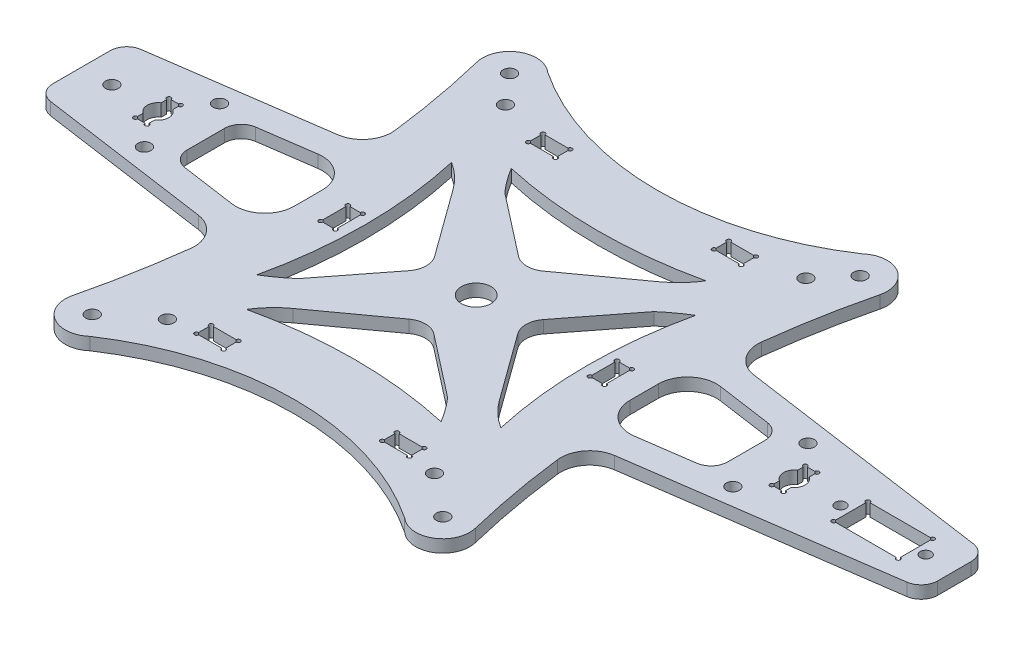
SolidWorks part; units mm, degrees
material "PPS"
ref_plane "前视基准面" through (0, 0, 0) normal (0, 0, 1) x (1, 0, 0)
ref_plane "上视基准面" through (0, 0, 0) normal (0, 1, 0) x (1, 0, 0)
ref_plane "右视基准面" through (0, 0, 0) normal (1, 0, 0) x (0, 0, -1)
sketch "草图1" plane through (0, 0, 0) normal (0, 1, 0) x (1, 0, 0)
  line L3 (-133.7177, 0) -> (146.3754, 0) construction
  line L56 (0, 96.0639) -> (0, -115.1457) construction
  line L65 (-25.5, 41.5) -> (-19, 41.5)
  line L66 (-34, 3.25) -> (-30.5, 3.25)
  line L70 (-34, 3.25) -> (-34, -3.25)
  line L76 (-34, -3.25) -> (-30.5, -3.25)
  line L80 (-30.5, 3.25) -> (-30.5, -3.25)
  line L81 (-25.5, -38) -> (-19, -38)
  line L82 (-25.5, -38) -> (-25.5, -41.5)
  line L83 (-25.5, -41.5) -> (-19, -41.5)
  line L84 (-19, -38) -> (-19, -41.5)
  line L85 (-19, 38) -> (-19, 41.5)
  line L86 (-25.5, 38) -> (-19, 38)
  line L142 (-25.5, 38) -> (-25.5, 41.5)
  line L143 (25.5, 38) -> (25.5, 41.5)
  line L144 (25.5, 38) -> (19, 38)
  line L145 (19, 38) -> (19, 41.5)
  line L146 (19, -38) -> (19, -41.5)
  line L147 (25.5, -41.5) -> (19, -41.5)
  line L148 (25.5, -38) -> (25.5, -41.5)
  line L149 (25.5, -38) -> (19, -38)
  line L150 (30.5, 3.25) -> (30.5, -3.25)
  line L151 (34, -3.25) -> (30.5, -3.25)
  line L152 (34, 3.25) -> (34, -3.25)
  line L153 (34, 3.25) -> (30.5, 3.25)
  line L154 (25.5, 41.5) -> (19, 41.5)
  line L155 (77.65, -2.1518) -> (77.65, -4)
  line L156 (74.85, 4) -> (77.65, 4)
  line L157 (74.85, 4) -> (74.85, 2.1768)
  line L158 (74.85, -4) -> (77.65, -4)
  line L159 (77.65, 4) -> (77.65, 2.1518)
  line L160 (74.85, -2.1768) -> (74.85, -4)
  line L161 (97.5, 7.6653) -> (97.5, -9.1503) construction
  line L162 (89.75, 4.1) -> (105.25, 4.1)
  line L163 (89.75, 4.1) -> (89.75, -4.1)
  line L164 (89.75, -4.1) -> (105.25, -4.1)
  line L165 (105.25, 4.1) -> (105.25, -4.1)
  line L166 (-97.5, 7.6653) -> (-97.5, -9.1503) construction
  line L171 (-74.85, -2.1768) -> (-74.85, -4)
  line L172 (-77.65, 4) -> (-77.65, 2.1518)
  line L173 (-74.85, -4) -> (-77.65, -4)
  line L174 (-74.85, 4) -> (-74.85, 2.1768)
  line L175 (-74.85, 4) -> (-77.65, 4)
  line L176 (-77.65, -2.1518) -> (-77.65, -4)
  line L177 (114.5911, 7.4683) -> (114.5911, -7.4683)
  line L178 (114.5911, 7.4683) -> (43.1936, 17.6463)
  line L179 (114.5911, -7.4683) -> (43.1936, -17.6463)
  line L183 (-24.7128, 19.184) -> (-10.803, 0)
  line L184 (19.184, 24.7128) -> (0, 10.803)
  line L185 (-24.7128, -17.8765) -> (-10.803, 0)
  line L186 (-17.8765, 24.7128) -> (0, 10.803)
  line L187 (24.7128, -19.184) -> (10.803, 0)
  line L188 (24.7128, 17.8765) -> (10.803, 0)
  line L189 (-19.184, -24.7128) -> (0, -10.803)
  line L190 (17.8765, -24.7128) -> (0, -10.803)
  line L191 (-94.5795, 10.321) -> (-94.5795, -10.321)
  line L192 (-43.1936, 17.6463) -> (-94.5795, 10.321)
  line L193 (-94.5795, -10.321) -> (-43.1936, -17.6463)
  line L195 (-64.75, -7.9571) -> (-64.75, 7.9571)
  line L196 (-64.75, 7.9571) -> (-40.25, 11.4497)
  line L197 (-40.25, 11.4497) -> (-40.25, -11.4497)
  line L198 (-64.75, -7.9571) -> (-40.25, -11.4497)
  line L199 (64.75, 7.9571) -> (40.25, 11.4497)
  line L200 (40.25, 11.4497) -> (40.25, -11.4497)
  line L201 (64.75, -7.9571) -> (40.25, -11.4497)
  line L202 (64.75, 7.9571) -> (64.75, -7.9571)
  circle A0 centre (-36, 43) radius 1.55
  circle A1 centre (-32, -42) radius 1.55
  circle A2 centre (32, -42) radius 1.55
  circle A3 centre (36, 43) radius 1.55
  circle A4 centre (42, 50) radius 1.55
  circle A5 centre (42, -50) radius 1.55
  circle A6 centre (-42, -50) radius 1.55
  circle A7 centre (-42, 50) radius 1.55
  arc A8 (74.85, 2.1768) -> (74.85, -2.1768) centre (76.2307, 0) ccw
  arc A9 (77.65, -2.1518) -> (77.65, 2.1518) centre (76.2307, 0) ccw
  circle A10 centre (107.7, 0) radius 1.3
  circle A11 centre (87.3, 0) radius 1.3
  circle A12 centre (-87.3, 0) radius 1.3 construction
  arc A14 (-77.65, -2.1518) -> (-77.65, 2.1518) centre (-76.2307, 0) cw
  arc A15 (-74.85, 2.1768) -> (-74.85, -2.1768) centre (-76.2307, 0) cw
  arc A18 (-37.7098, 54.831) -> (37.7098, 54.831) centre (0, 111.5317) ccw
  arc A20 (48.2756, 48.4632) -> (43.1936, 17.6463) centre (246.1791, 0) ccw
  arc A21 (48.2756, 48.4632) -> (37.7098, 54.831) centre (42, 50) ccw
  arc A22 (-37.7098, -54.831) -> (37.7098, -54.831) centre (0, -111.5317) cw
  arc A23 (48.2756, -48.4632) -> (43.1936, -17.6463) centre (246.1791, 0) cw
  arc A24 (48.2756, -48.4632) -> (37.7098, -54.831) centre (42, -50) cw
  arc A26 (-48.2756, -48.4632) -> (-37.7098, -54.831) centre (-42, -50) ccw
  arc A27 (-48.2756, -48.4632) -> (-43.1936, -17.6463) centre (-246.1791, 0) ccw
  arc A28 (-48.2756, 48.4632) -> (-37.7098, 54.831) centre (-42, 50) cw
  arc A30 (-48.2756, 48.4632) -> (-43.1936, 17.6463) centre (-246.1791, 0) cw
  arc A31 (-24.7128, 19.184) -> (-30.4857, 24.5725) centre (-41.4252, 7.0662) ccw
  arc A32 (-24.7128, -17.8765) -> (-30.4857, -22.0817) centre (-52.1779, 13.7617) cw
  arc A33 (-30.4857, -22.0817) -> (-30.4857, 24.5725) centre (-134.387, 1.2454) ccw
  arc A34 (-17.8765, 24.7128) -> (-22.0817, 30.4857) centre (13.7617, 52.1779) cw
  arc A35 (-22.0817, 30.4857) -> (24.5725, 30.4857) centre (1.2454, 134.387) ccw
  arc A36 (19.184, 24.7128) -> (24.5725, 30.4857) centre (7.0662, 41.4252) ccw
  arc A37 (24.7128, 17.8765) -> (30.4857, 22.0817) centre (52.1779, -13.7617) cw
  arc A38 (30.4857, 22.0817) -> (30.4857, -24.5725) centre (134.387, -1.2454) ccw
  arc A39 (24.7128, -19.184) -> (30.4857, -24.5725) centre (41.4252, -7.0662) ccw
  arc A40 (17.8765, -24.7128) -> (22.0817, -30.4857) centre (-13.7617, -52.1779) cw
  arc A41 (22.0817, -30.4857) -> (-24.5725, -30.4857) centre (-1.2454, -134.387) ccw
  arc A42 (-19.184, -24.7128) -> (-24.5725, -30.4857) centre (-7.0662, -41.4252) ccw
  circle A43 centre (70.5, 9) radius 1.55
  circle A44 centre (70.5, -9) radius 1.55
  circle A45 centre (-70.5, -9) radius 1.55
  circle A46 centre (-70.5, 9) radius 1.55
  circle A47 centre (-87.3, 0) radius 1.55
  point P81 (-34, 0)
  point P118 (0, 0)
  point P140 (-40.25, 0)
  point P149 (-64.75, 0)
  dimension "D5" = 38
  dimension "D18" = 8.2
  dimension "D24" = 3.1
  dimension "D6" = 3.1
  dimension "D11" = 50
  dimension "D15" = 74.85
  dimension "D16" = 2.6
  dimension "D17" = 15.5
  dimension "D21" = 3.1
  dimension "D1" = 6.5
  dimension "D2" = 3.5
  dimension "D3" = 30.5
  dimension "D4" = 19
  dimension "D7" = 32
  dimension "D8" = 42
  dimension "D9" = 43
  dimension "D10" = 36
  dimension "D12" = 42
  dimension "D13" = 2.8
  dimension "D14" = 4
  dimension "D19" = 2.45
  dimension "D20" = 97.5
  dimension "D22" = 9
  dimension "D23" = 70.5
  dimension "D25" = 6.55
  dimension "D26" = 5.75
  dimension "D27" = 6.25
  dimension "D28" = 4
extrude "凸台-拉伸1" add sketch "草图1" along normal blind 3
fillet "圆角1" radius 4 8 edges at (114.5911, 1.5, -7.4683) (114.5911, 1.5, 7.4683) (-94.5795, 1.5, 10.321) (-94.5795, 1.5, -10.321) (-64.75, 1.5, 7.9571) (-64.75, 1.5, -7.9571) (64.75, 1.5, 7.9571) (64.75, 1.5, -7.9571)
fillet "圆角2" radius 7 8 edges at (43.1936, 1.5, -17.6463) (43.1936, 1.5, 17.6463) (-43.1936, 1.5, 17.6463) (-43.1936, 1.5, -17.6463) (40.25, 1.5, 11.4497) (40.25, 1.5, -11.4497) (-40.25, 1.5, 11.4497) (-40.25, 1.5, -11.4497)
sketch "草图2" plane through (0, 3, 0) normal (0, 1, 0) x (1, 0, 0)
  line L0 (0, 0) -> (0, -66.7571) construction
  circle A0 centre (-77.65, 4) radius 0.5
  circle A1 centre (-74.85, 4) radius 0.5
  circle A2 centre (-77.65, -4) radius 0.5
  circle A3 centre (-74.85, -4) radius 0.5
  circle A4 centre (-25.5, 41.5) radius 0.5
  circle A5 centre (-19, 41.5) radius 0.5
  circle A6 centre (-25.5, 38) radius 0.5
  circle A7 centre (-19, 38) radius 0.5
  circle A8 centre (-34, 3.25) radius 0.5
  circle A9 centre (-30.5, 3.25) radius 0.5
  circle A10 centre (-34, -3.25) radius 0.5
  circle A11 centre (-30.5, -3.25) radius 0.5
  circle A12 centre (-25.5, -38) radius 0.5
  circle A13 centre (-19, -38) radius 0.5
  circle A14 centre (-25.5, -41.5) radius 0.5
  circle A15 centre (-19, -41.5) radius 0.5
  circle A16 centre (19, -41.5) radius 0.5
  circle A17 centre (25.5, -41.5) radius 0.5
  circle A18 centre (19, -38) radius 0.5
  circle A19 centre (25.5, -38) radius 0.5
  circle A20 centre (30.5, -3.25) radius 0.5
  circle A21 centre (34, -3.25) radius 0.5
  circle A22 centre (30.5, 3.25) radius 0.5
  circle A23 centre (34, 3.25) radius 0.5
  circle A24 centre (19, 38) radius 0.5
  circle A25 centre (25.5, 38) radius 0.5
  circle A26 centre (19, 41.5) radius 0.5
  circle A27 centre (25.5, 41.5) radius 0.5
  circle A28 centre (74.85, -4) radius 0.5
  circle A29 centre (77.65, -4) radius 0.5
  circle A30 centre (74.85, 4) radius 0.5
  circle A31 centre (77.65, 4) radius 0.5
  circle A32 centre (89.75, 4.1) radius 0.5
  circle A33 centre (105.25, 4.1) radius 0.5
  circle A34 centre (89.75, -4.1) radius 0.5
  circle A35 centre (105.25, -4.1) radius 0.5
  dimension "D1" = 1
extrude "直角约束" cut sketch "草图2" against normal through all
sketch "草图3" plane through (0, 0, 0) normal (0, 1, 0) x (1, 0, 0)
  circle A0 centre (0, 0) radius 3.55
  dimension "D1" = 7.1
extrude "切除-拉伸2" cut sketch "草图3" along normal through all
fillet "圆角3" radius 5 4 edges at (0, 1.5, 10.803) (10.803, 1.5, 0) (0, 1.5, -10.803) (-10.803, 1.5, 0)
